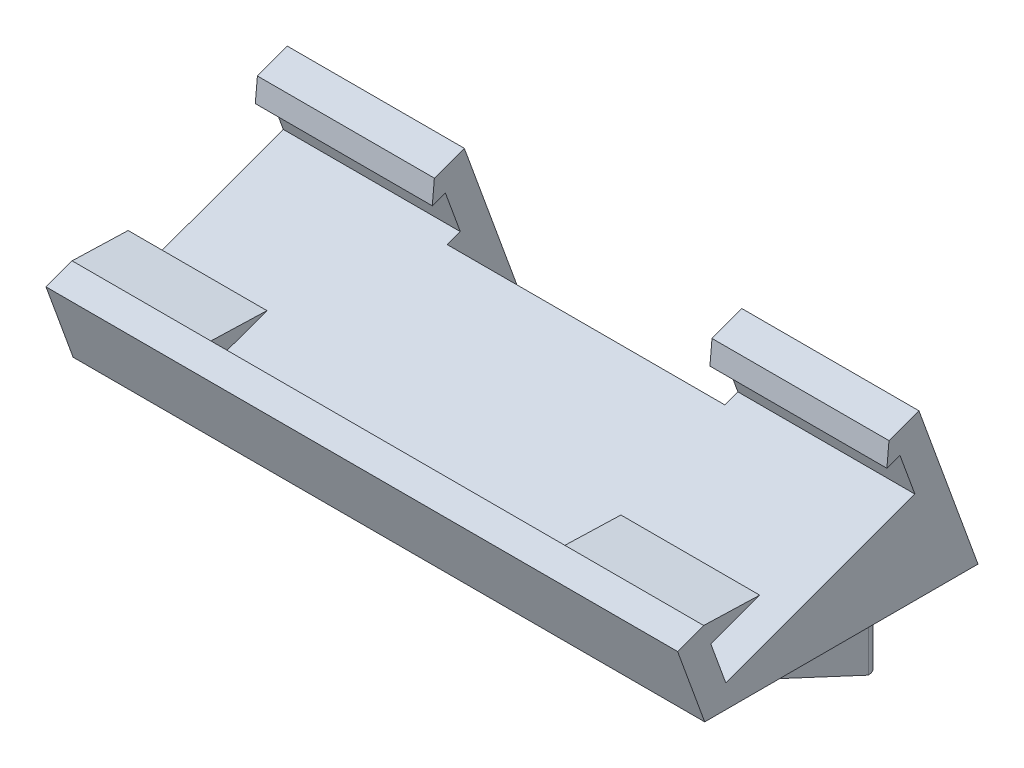
SolidWorks part; units mm, degrees
ref_plane "Front Plane" through (0, 0, 0) normal (0, 0, 1) x (1, 0, 0)
ref_plane "Top Plane" through (0, 0, 0) normal (0, 1, 0) x (1, 0, 0)
ref_plane "Right Plane" through (0, 0, 0) normal (1, 0, 0) x (0, 0, -1)
sketch "Sketch2" plane through (0, 0, 0) normal (1, 0, 0) x (0, 0, -1)
  line L0 (-17.3843, 0) -> (17.3843, 0) construction
  line L1 (17.3843, 0) -> (17.3843, 14.6547) construction
  line L2 (17.3843, 14.6547) -> (-17.3843, 2) construction
  line L3 (-17.3843, 2) -> (-17.3843, 0) construction
  line L4 (-13.6255, 3.3681) -> (-15.7803, 9.2881)
  line L5 (-15.7803, 9.2881) -> (-8.7326, 11.8533)
  line L6 (-16.8063, 12.1072) -> (-8.7326, 11.8533)
  line L7 (-16.8063, 12.1072) -> (-20.5651, 10.7391)
  line L8 (-20.5651, 10.7391) -> (-17.3843, 2)
  line L9 (-17.3843, 2) -> (-16.6564, 0)
  line L10 (-13.6255, 3.3681) -> (13.6255, 13.2867)
  line L11 (9.8914, 21.8244) -> (14.2035, 23.3939)
  line L12 (14.2035, 23.3939) -> (17.3843, 14.6547)
  line L13 (13.6255, 13.2867) -> (11.4708, 19.2067)
  line L14 (11.4708, 19.2067) -> (9.5914, 18.5227)
  line L15 (9.8914, 21.8244) -> (9.5914, 18.5227)
  line L16 (17.3843, 14.6547) -> (22.7182, 0)
  line L17 (-16.6564, 0) -> (22.7182, 0)
  point P4 (0, 0)
  dimension "D1" = 37
  dimension "D2" = 2
  dimension "D3" = 20
  dimension "D4" = 6.3
  dimension "D5" = 4
  dimension "D6" = 4
  dimension "D7" = 3
  dimension "D8" = 7.5
  dimension "D9" = 2
  dimension "D10" = 0.3
  dimension "D11" = 4
  dimension "D12" = 3
extrude "Boss-Extrude1" add sketch "Sketch2" along normal mid plane 91
sketch "Sketch3" plane through (0, 16.0924, 5.8572) normal (0, 0.9397, 0.342) x (1, 0, 0)
  line L0 (-45.5, -11.6519) -> (-45.5, -15.6519) construction
  line L1 (-45.5, -15.6519) -> (45.5, -15.6519) construction
  line L2 (45.5, -15.6519) -> (45.5, -11.6519) construction
  line L3 (-45.5, -4.1519) -> (-45.5, -11.6519) construction
  line L4 (45.5, -11.6519) -> (45.5, -4.1519) construction
  line L5 (45.5, -4.1519) -> (-45.5, -4.1519) construction
  line L6 (-45.5, -11.6519) -> (-45.5, -15.6519) construction
  line L7 (-45.5, -15.6519) -> (45.5, -15.6519) construction
  line L8 (45.5, -15.6519) -> (45.5, -11.6519) construction
  line L9 (-45.5, -4.1519) -> (-45.5, -11.6519) construction
  line L10 (45.5, -11.6519) -> (45.5, -4.1519) construction
  line L11 (45.5, -4.1519) -> (-45.5, -4.1519) construction
  line L12 (45.5, -11.6519) -> (-45.5, -11.6519) construction
  line L13 (45.5, -11.6519) -> (-45.5, -11.6519) construction
  line L14 (-45.5, 16.7593) -> (-45.5, 15.3481) construction
  line L15 (-25.5, -4.1519) -> (25.5, -4.1519)
  line L16 (-25.5, -4.1519) -> (-25.5, -11.6519)
  line L17 (-25.5, -11.6519) -> (25.5, -11.6519)
  line L18 (25.5, -4.1519) -> (25.5, -11.6519)
  line L19 (-45.5, 15.3481) -> (45.5, 15.3481) construction
  line L20 (45.5, 15.3481) -> (45.5, 16.7593) construction
  line L21 (-45.5, 21.3481) -> (-45.5, 16.7593) construction
  line L22 (45.5, 16.7593) -> (45.5, 21.3481) construction
  line L23 (45.5, 21.3481) -> (-45.5, 21.3481) construction
  line L24 (-45.5, 16.7593) -> (-45.5, 15.3481) construction
  line L25 (-45.5, 15.3481) -> (45.5, 15.3481) construction
  line L26 (45.5, 15.3481) -> (45.5, 16.7593) construction
  line L27 (-45.5, 21.3481) -> (-45.5, 16.7593) construction
  line L28 (45.5, 16.7593) -> (45.5, 21.3481) construction
  line L29 (45.5, 21.3481) -> (-45.5, 21.3481) construction
  line L30 (45.5, 16.7593) -> (-45.5, 16.7593) construction
  line L31 (45.5, 16.7593) -> (-45.5, 16.7593) construction
  line L33 (-20, 21.3481) -> (20, 21.3481)
  line L34 (-20, 21.3481) -> (-20, 15.3481)
  line L35 (-20, 15.3481) -> (20, 15.3481)
  line L36 (20, 21.3481) -> (20, 15.3481)
  point P10 (0, -11.6519)
  point P11 (0, -15.6519)
  point P22 (0, 21.3481)
  point P23 (0, 21.3481)
  dimension "D1" = 20
  dimension "D2" = 40
extrude "Cut-Extrude1" cut sketch "Sketch3" against normal up to next
sketch "Sketch4" plane through (0, 0, 0) normal (0, -1, 0) x (1, 0, 0)
  line L0 (-45.5, 16.6564) -> (-45.5, -22.7182) construction
  line L1 (42, -12.6809) -> (-42, -12.6809) construction
  line L2 (42, -12.6809) -> (42, 6.6191) construction
  line L3 (42, 6.6191) -> (-42, 6.6191) construction
  line L4 (-42, -12.6809) -> (-42, 6.6191) construction
  line L5 (42, -12.6809) -> (-42, 6.6191) construction
  line L6 (42, 6.6191) -> (-42, -12.6809) construction
  line L7 (-45.5, 16.6564) -> (-45.5, -22.7182) construction
  line L8 (45.5, 16.6564) -> (-45.5, 16.6564) construction
  line L9 (38.1, -12.6809) -> (38.1, 6.6191) construction
  line L10 (39.775, 4.8941) -> (39.775, -10.9559) construction
  line L11 (41.45, 4.8941) -> (41.45, -10.9559)
  line L12 (38.1, 4.8941) -> (38.1, -10.9559)
  line L13 (0, -55) -> (0, 55) construction
  line L14 (-39.775, 4.8941) -> (-39.775, -10.9559) construction
  line L15 (-41.45, 4.8941) -> (-41.45, -10.9559)
  line L16 (-38.1, 4.8941) -> (-38.1, -10.9559)
  arc A4 (-41.45, 4.8941) -> (-38.1, 4.8941) centre (-39.775, 4.8941) cw
  arc A5 (41.45, 4.8941) -> (38.1, 4.8941) centre (39.775, 4.8941) ccw
  arc A6 (38.1, -10.9559) -> (41.45, -10.9559) centre (39.775, -10.9559) ccw
  arc A7 (-38.1, -10.9559) -> (-41.45, -10.9559) centre (-39.775, -10.9559) cw
  point P0 (0, -3.0309)
  point P9 (39.775, -3.0309)
  point P10 (-45.5, -3.0309)
  point P13 (0, 16.6564)
  point P20 (42, -3.0309)
  point P21 (39.775, 6.5691)
  point P22 (39.775, -12.6309)
  point P23 (38.1, -3.0309)
  point P28 (-39.775, -3.0309)
  dimension "D4" = 3.35
  dimension "D1" = 19.3
  dimension "D2" = 84
  dimension "D3" = 38.1
  dimension "D5" = 19.2
extrude "Boss-Extrude2" add sketch "Sketch4" along normal blind 10
sketch "Sketch5" plane through (41.45, 0, 0) normal (1, 0, 0) x (0, 0, -1)
  line L0 (-6.5691, -1.828) -> (10.9559, -10)
  line L1 (-6.5691, 0) -> (-6.5691, -10) construction
  line L2 (10.9559, -10) -> (-4.8941, -10) construction
  line L3 (10.9559, -10) -> (-6.5691, -10)
  line L4 (-6.5691, -10) -> (-6.5691, -1.828)
  dimension "D1" = 25
extrude "Cut-Extrude3" cut sketch "Sketch5" against normal through all
equation "\"CAMy\"= 29mm"
equation "\"CAMx\"= 81"
equation "\"D1@Boss-Extrude1\"=\"CAMx\"+10"
